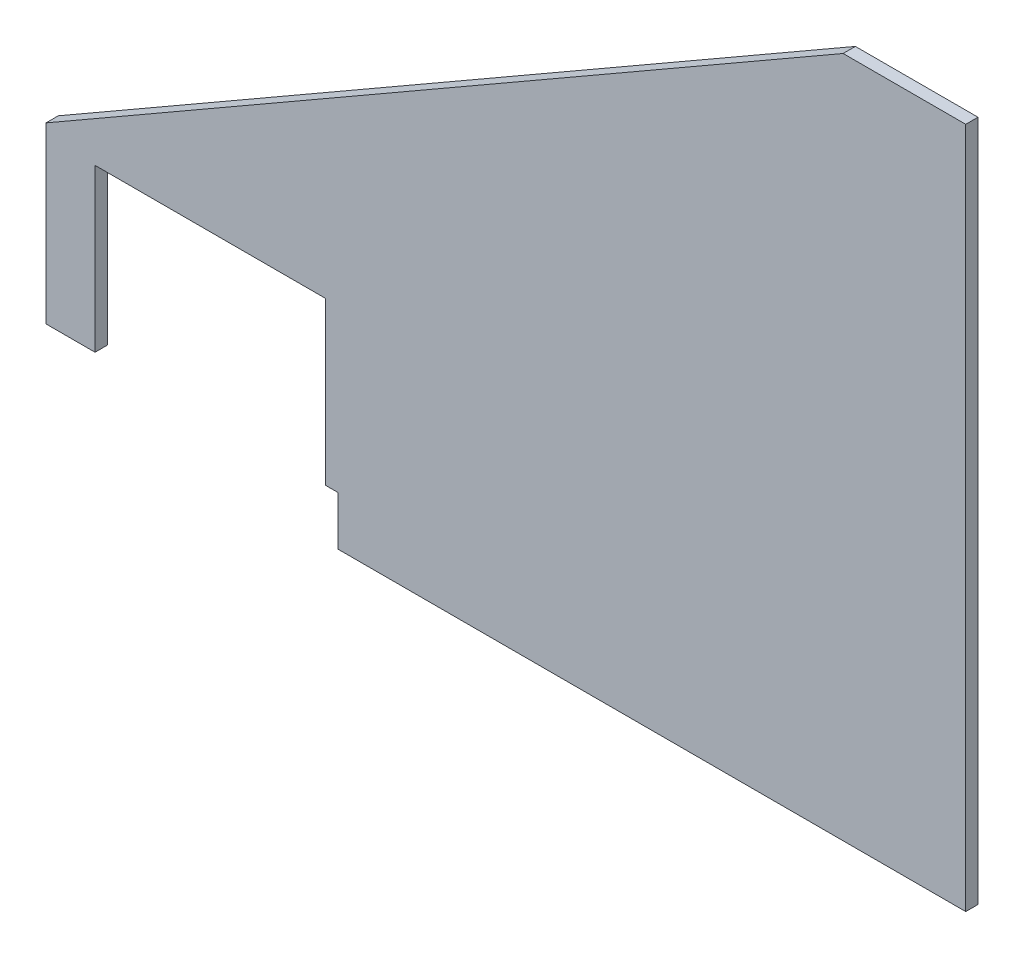
SolidWorks part; units mm, degrees
ref_plane "정면" through (0, 0, 0) normal (0, 0, 1) x (1, 0, 0)
ref_plane "윗면" through (0, 0, 0) normal (0, 1, 0) x (1, 0, 0)
ref_plane "우측면" through (0, 0, 0) normal (1, 0, 0) x (0, 0, -1)
sketch "스케치1" plane through (0, 0, 0) normal (0, 0, 1) x (1, 0, 0)
  line L0 (-128, -139) -> (128, -139)
  line L1 (128, -139) -> (128, 139)
  line L2 (128, 139) -> (78, 139)
  line L3 (78, 139) -> (-247, -48)
  line L7 (-128, -139) -> (-128, -119)
  line L8 (-133, -53) -> (-227, -53)
  line L11 (-247, -48) -> (-247, -119)
  line L12 (-247, -119) -> (-227, -119)
  line L13 (-227, -53) -> (-227, -119)
  line L14 (-128, -119) -> (-133, -119)
  line L17 (-133, -119) -> (-133, -53)
  point P3 (128, 0)
  point P6 (0, -139)
  point P10 (0, 0)
  point P15 (0, 0)
  dimension "D1" = 278
  dimension "D2" = 91
  dimension "D3" = 375
  dimension "D4" = 50
  dimension "D5" = 256
  dimension "D6" = 20
  dimension "D7" = 71
  dimension "D8" = 5
  dimension "D9" = 86
extrude "보스-돌출1" add sketch "스케치1" along normal blind 5 contours L3 L11 L12 L13 L8 L17 L14 L7 L0 L1 L2
